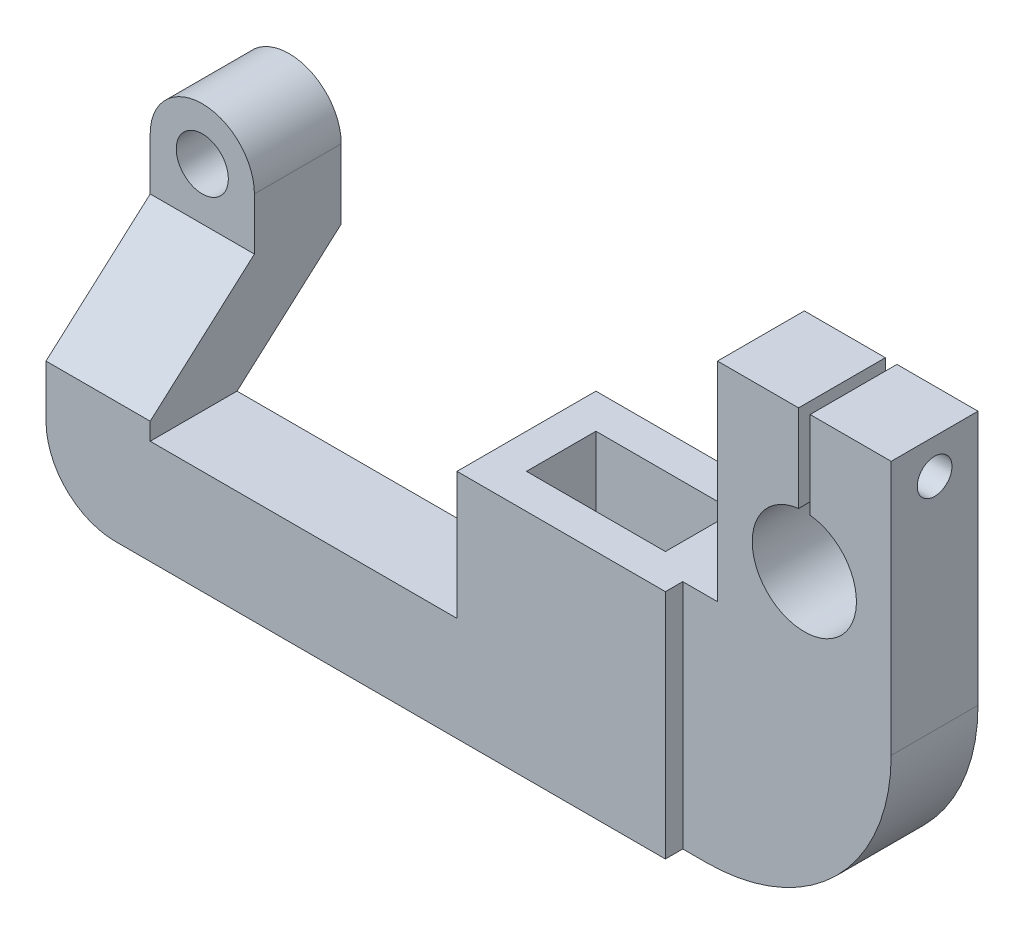
SolidWorks part; units mm, degrees
ref_plane "Front Plane" through (0, 0, 0) normal (0, 0, 1) x (1, 0, 0)
ref_plane "Top Plane" through (0, 0, 0) normal (0, 1, 0) x (1, 0, 0)
ref_plane "Right Plane" through (0, 0, 0) normal (1, 0, 0) x (0, 0, -1)
sketch "Sketch2" plane through (0, 0, 0) normal (0, 0, 1) x (1, 0, 0)
  line L0 (-78.063, 34.6446) -> (-78.063, 25.6446)
  line L1 (-60.063, 34.6446) -> (-60.063, 25.6446)
  line L2 (-60.063, 25.6446) -> (-78.063, 25.6446)
  arc A0 (-60.063, 34.6446) -> (-78.063, 34.6446) centre (-69.063, 34.6446) ccw
  circle A2 centre (-69.063, 34.6446) radius 4.5
extrude "Boss-Extrude1" add sketch "Sketch2" against normal blind 15
sketch "Sketch6" plane through (0, 0, -15) normal (0, 0, -1) x (-1, 0, 0)
  line L0 (60.063, 25.6446) -> (60.063, 22.6446)
  line L1 (60.063, 22.6446) -> (78.063, 22.6446)
  line L2 (78.063, 22.6446) -> (78.063, 25.6446)
  line L3 (60.063, 22.6446) -> (60.063, 6.6446)
  line L4 (60.063, 6.6446) -> (78.063, 6.6446)
  line L5 (78.063, 6.6446) -> (78.063, 22.6446)
  line M4 (60.063, 25.6446) -> (78.063, 25.6446)
extrude "Boss-Extrude9" add sketch "Sketch6" against normal blind 33 contours L4 L5 L1 L3 | L1 L2 L0 M4
sketch "Sketch15" plane through (-78.063, 0, 0) normal (-1, 0, 0) x (0, 0, 1)
  line L0 (-15, 6.6446) -> (-15, 22.6446)
  line L1 (-15, 34.6446) -> (-15, 6.6446) construction
  line L4 (18, 6.6446) -> (-15, 6.6446) construction
  line L5 (3, 6.6446) -> (-15, 22.6446)
  line L6 (3, 6.6446) -> (-15, 6.6446)
  line L9 (18, 9.6446) -> (0, 25.6446)
  line L10 (0, 25.6446) -> (18, 25.6446)
  line L11 (18, 25.6446) -> (18, 9.6446)
extrude "Cut-Extrude2" cut sketch "Sketch15" against normal blind 33
sketch "Sketch16" plane through (0, 0, 18) normal (0, 0, 1) x (1, 0, 0)
  line L0 (-78.063, 6.6446) -> (-78.063, 0.6446)
  line L1 (-66.063, -11.3554) -> (-7.063, -11.3554)
  line L3 (-7.063, 6.6446) -> (-78.063, 6.6446)
  line L4 (-7.063, 6.6446) -> (-7.063, -11.3554)
  arc A0 (-66.063, -11.3554) -> (-78.063, 0.6446) centre (-66.063, 0.6446) cw
  dimension "D1" = 12
extrude "Boss-Extrude11" add sketch "Sketch16" against normal blind 15
sketch "Sketch18" plane through (0, 0, 18) normal (0, 0, 1) x (1, 0, 0)
  line L0 (-7.063, 6.6446) -> (-7.063, 28.6446)
  line L1 (-7.063, 28.6446) -> (28.937, 28.6446)
  line L2 (28.937, 28.6446) -> (28.937, -11.3554)
  line L3 (28.937, -11.3554) -> (-7.063, -11.3554)
  line L4 (-7.063, 6.6446) -> (-7.063, -11.3554)
  line L5 (-7.063, 6.6446) -> (-7.063, -11.3554)
  line L10 (-60.063, 6.6446) -> (-60.063, 9.6446)
  line L11 (-60.063, 9.6446) -> (-78.063, 9.6446)
  line L12 (-78.063, 9.6446) -> (-78.063, 0.6446)
  line L13 (-66.063, -11.3554) -> (-7.063, -11.3554)
  line L14 (-7.063, -11.3554) -> (-7.063, 6.6446)
  line L15 (-7.063, 6.6446) -> (-60.063, 6.6446)
  line L16 (-60.063, 6.6446) -> (-60.063, 9.6446)
  line L17 (-60.063, 9.6446) -> (-78.063, 9.6446)
  line L18 (-78.063, 9.6446) -> (-78.063, 0.6446)
  line L19 (-66.063, -11.3554) -> (-7.063, -11.3554)
  line L21 (-7.063, 6.6446) -> (-60.063, 6.6446)
  arc A1 (-78.063, 0.6446) -> (-66.063, -11.3554) centre (-66.063, 0.6446) ccw
  arc A2 (-78.063, 0.6446) -> (-66.063, -11.3554) centre (-66.063, 0.6446) ccw
  line M6 (-7.063, -11.3554) -> (-7.063, 6.6446)
  dimension "D1" = 0
extrude "Boss-Extrude13" add sketch "Sketch18" against normal blind 24 contours L3 L2 L1 L0 M6
sketch "Sketch20" plane through (0, 28.6446, 0) normal (0, 1, 0) x (1, 0, 0)
  line L0 (-7.063, 6) -> (28.937, 6) construction
  line L1 (-1.063, 0) -> (22.937, 0)
  line L2 (-1.063, 0) -> (-1.063, -12)
  line L3 (-1.063, -12) -> (22.937, -12)
  line L4 (22.937, 0) -> (22.937, -12)
  line L5 (-7.063, 6) -> (-7.063, -18) construction
  dimension "D1" = 6
  dimension "D2" = 6
extrude "Cut-Extrude3" cut sketch "Sketch20" against normal blind 57
sketch "Sketch21" plane through (0, 0, 0) normal (0, 0, 1) x (1, 0, 0)
  line L0 (22.937, 28.6446) -> (34.937, 28.6446)
  line L3 (22.937, 28.6446) -> (22.937, -11.3554)
  line L4 (22.937, -11.3554) -> (32.937, -11.3554)
  line L5 (64.937, 20.6446) -> (64.937, 64.6446)
  line L6 (64.937, 64.6446) -> (50.937, 64.6446)
  line L7 (34.937, 64.6446) -> (34.937, 28.6446)
  line L10 (48.937, 64.6446) -> (48.937, 49.5889)
  line L12 (50.937, 64.6446) -> (50.937, 49.5889)
  line L13 (48.937, 64.6446) -> (34.937, 64.6446)
  arc A0 (48.937, 49.5889) -> (50.937, 49.5889) centre (49.937, 40.6446) ccw
  arc A1 (32.937, -11.3554) -> (64.937, 20.6446) centre (32.937, 20.6446) ccw
  dimension "D1" = 32
  dimension "D2" = 12
  dimension "D3" = 15
  dimension "D4" = 24
extrude "Boss-Extrude15" add sketch "Sketch21" along normal blind 15
sketch "Sketch22" plane through (64.937, 0, 0) normal (1, 0, 0) x (0, 0, -1)
  line L0 (-15, 64.6446) -> (0, 64.6446) construction
  line L1 (0, 20.6446) -> (0, 64.6446) construction
  circle A0 centre (-7.5, 58.6446) radius 3
  dimension "D1" = 6
  dimension "D2" = 7.5
extrude "Cut-Extrude4" cut sketch "Sketch22" against normal blind 47
